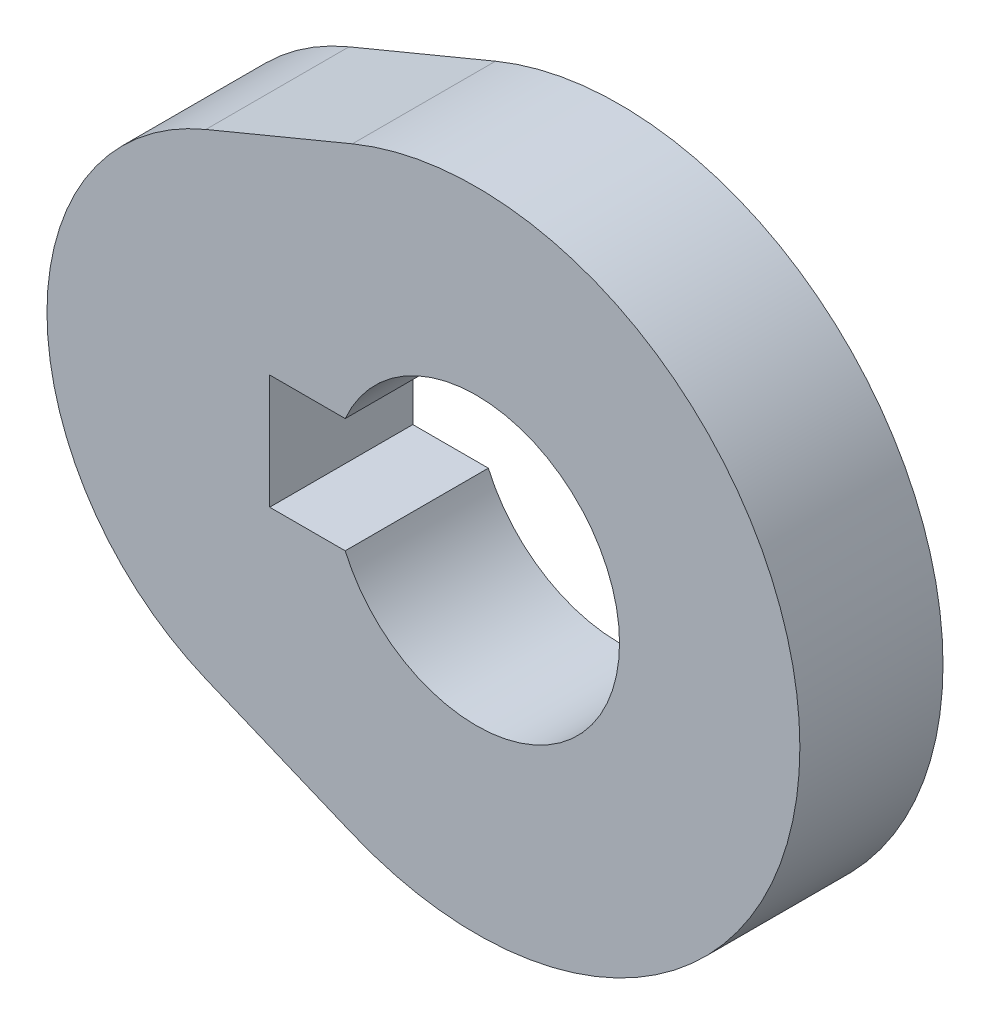
SolidWorks part; units mm, degrees
ref_plane "Front Plane" through (0, 0, 0) normal (0, 0, 1) x (1, 0, 0)
ref_plane "Top Plane" through (0, 0, 0) normal (0, 1, 0) x (1, 0, 0)
ref_plane "Right Plane" through (0, 0, 0) normal (1, 0, 0) x (0, 0, -1)
sketch "Sketch3" plane through (0, 0, 0) normal (0, 0, 1) x (1, 0, 0)
  line L0 (0, 0) -> (-26.3, 0) construction
  line L1 (-20.75, 8.3125) -> (-15.6317, 10.4368)
  line L2 (-20.75, -8.3125) -> (-15.6317, -10.4368)
  line L4 (-14.08, -2) -> (-18.52, -2)
  line L5 (-14.08, -2) -> (-14.08, 2)
  line L6 (-14.08, 2) -> (-18.52, 2)
  line L7 (-18.52, -2) -> (-18.52, 2)
  line L8 (-14.08, -2) -> (-18.52, 2) construction
  line L9 (-14.08, 2) -> (-18.52, -2) construction
  circle A0 centre (-11.3, 0) radius 11.3
  circle A1 centre (-17.3, 0) radius 9
  circle A2 centre (-11.3, 0) radius 5
  point P12 (-16.3, 0)
  point P17 (0, 0)
  dimension "D2" = 22.6
  dimension "D3" = 18
  dimension "D4" = 10
  dimension "D5" = 4
  dimension "D6" = 7.22
  dimension "D1" = 15
extrude "Boss-Extrude2" add sketch "Sketch3" along normal blind 5 contours A2 L4 A1 A0 L6 | L6 A1 A0 L4 L7 | A1 L2 A0 | A0 A1 | A1 A0 L1
equation "\"D6@Sketch3\"=5+2.22"
